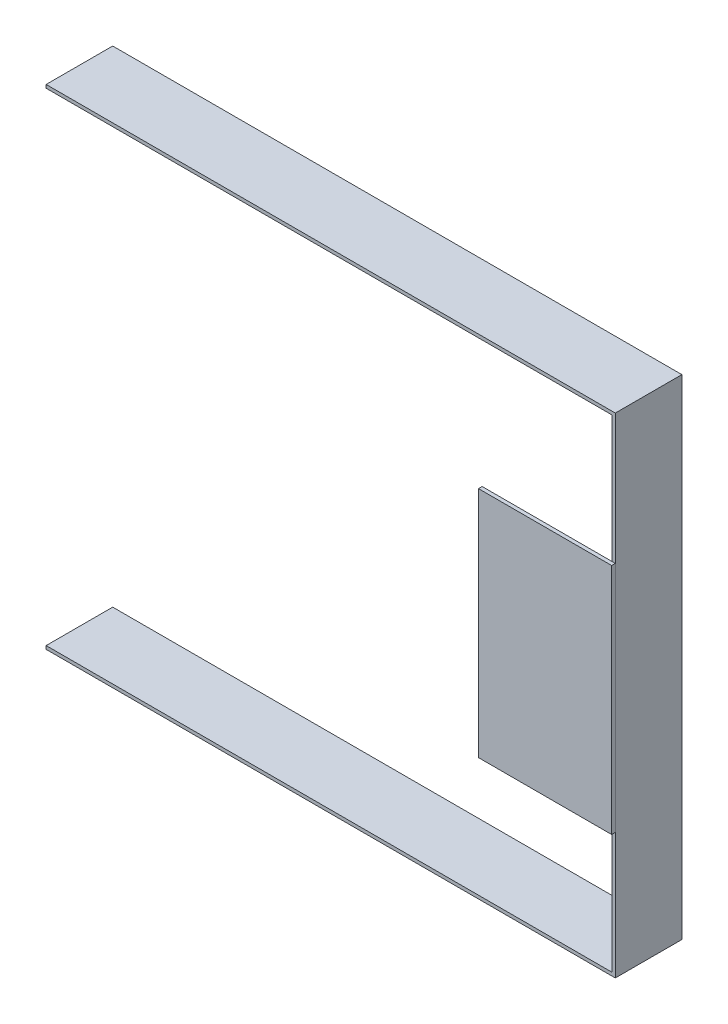
SolidWorks part; units mm, degrees
ref_plane "Front Plane" through (0, 0, 0) normal (0, 0, 1) x (1, 0, 0)
ref_plane "Top Plane" through (0, 0, 0) normal (0, 1, 0) x (1, 0, 0)
ref_plane "Right Plane" through (0, 0, 0) normal (1, 0, 0) x (0, 0, -1)
sketch "Sketch5" plane through (0, 0, 0) normal (0, 0, 1) x (1, 0, 0)
  line L0 (-181.6431, 42.2192) -> (250.1569, 42.2192)
  line L1 (250.1569, 42.2192) -> (250.1569, -326.0808)
  line L2 (250.1569, -326.0808) -> (-181.6431, -326.0808)
  line L3 (-181.6431, 44.7592) -> (252.6969, 44.7592)
  line L4 (252.6969, 44.7592) -> (252.6969, -328.6208)
  line L5 (252.6969, -328.6208) -> (-181.6431, -328.6208)
  line L6 (-181.6431, 44.7592) -> (-181.6431, 42.2192)
  line L7 (-181.6431, -326.0808) -> (-181.6431, -328.6208)
  dimension "D1" = 2.54
extrude "Boss-Extrude1" add sketch "Sketch5" along normal blind 50.8 contours L0 L1 L2 L7 L5 L4 L3 L6
sketch "Sketch6" plane through (252.6969, 0, 0) normal (1, 0, 0) x (0, 0, -1)
  line L0 (-50.8, 44.7592) -> (-50.8, -328.6208) construction
  line L1 (-50.8, -54.5984) -> (-53.594, -54.5984)
  line L2 (-50.8, -54.5984) -> (-50.8, -232.3984)
  line L3 (-50.8, -232.3984) -> (-53.594, -232.3984)
  line L4 (-53.594, -54.5984) -> (-53.594, -232.3984)
  dimension "D1" = 177.8
  dimension "D2" = 2.794
extrude "Boss-Extrude2" add sketch "Sketch6" against normal blind 101.6 separate body
